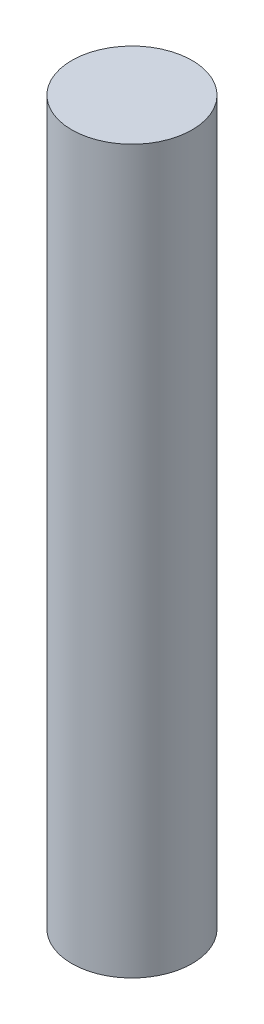
SolidWorks part; units mm, degrees
other "Preload Coupling Cross Pin"
ref_plane "Front Plane" through (0, 0, 0) normal (0, 0, 1) x (1, 0, 0)
ref_plane "Top Plane" through (0, 0, 0) normal (0, 1, 0) x (1, 0, 0)
ref_plane "Right Plane" through (0, 0, 0) normal (1, 0, 0) x (0, 0, -1)
sketch3d "Torque pin envelope sketch datum points"
  point P0 (-2, -35, -19.5)
  point P1 (8, -35, -19.5)
  point P2 (-2, -35, -29.5)
ref_plane "Torque pin envelope sketch plane" through (0, -35, 0) normal (0, 1, 0) x (1, 0, 0)
sketch "Torque pin envelope sketch" plane through (0, -35, 0) normal (0, 1, 0) x (1, 0, 0)
  circle A0 centre (-2, 19.5) radius 1
extrude "Torque pin envelope" add sketch "Torque pin envelope sketch" along normal blind 12 separate body
